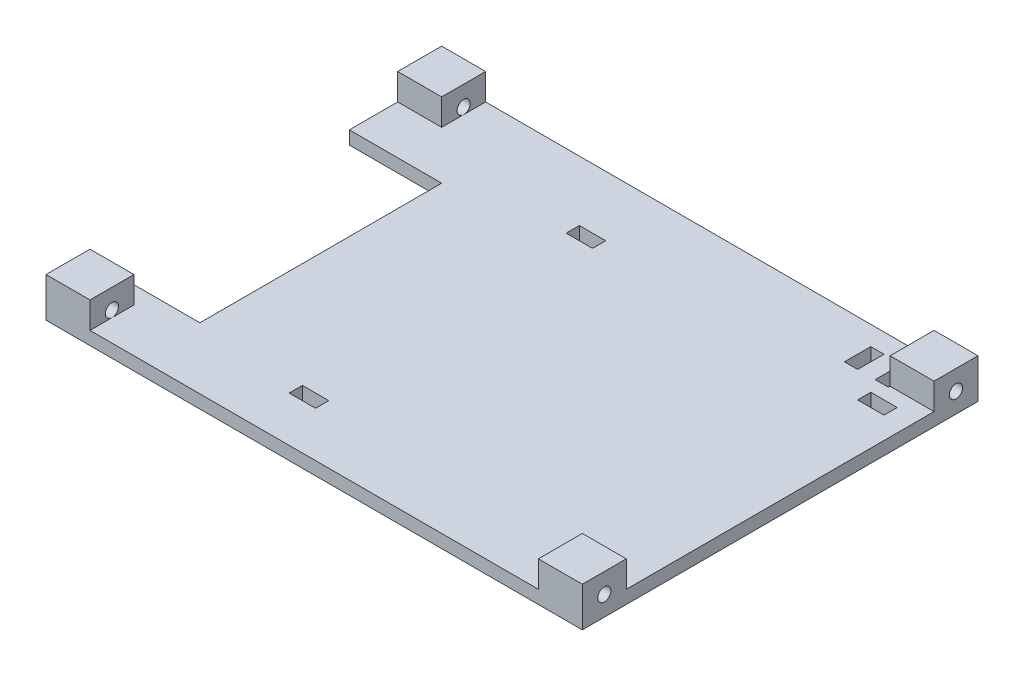
SolidWorks part; units mm, degrees
ref_plane "Front Plane" through (0, 0, 0) normal (0, 0, 1) x (1, 0, 0)
ref_plane "Top Plane" through (0, 0, 0) normal (0, 1, 0) x (1, 0, 0)
ref_plane "Right Plane" through (0, 0, 0) normal (1, 0, 0) x (0, 0, -1)
sketch "Sketch1" plane through (0, 0, 0) normal (0, 1, 0) x (1, 0, 0)
  line L1 (0, 0) -> (122, 0)
  line L2 (0, 0) -> (0, 90)
  line L3 (0, 90) -> (122, 90)
  line L4 (122, 0) -> (122, 90)
  dimension "D1" = 122
  dimension "D2" = 90
extrude "Boss-Extrude1" add sketch "Sketch1" along normal blind 3
sketch "Sketch2" plane through (0, 3, 0) normal (0, 1, 0) x (1, 0, 0)
  line L1 (0, 0) -> (10, 0)
  line L2 (0, 0) -> (0, 10)
  line L3 (0, 10) -> (7.7811, 10)
  line L4 (10, 0) -> (10, 5.7066)
  line L5 (0, 90) -> (10, 90)
  line L6 (0, 90) -> (0, 80)
  line L7 (0, 80) -> (10, 80)
  line L8 (10, 90) -> (10, 80)
  line L9 (122, 90) -> (112, 90)
  line L10 (122, 90) -> (122, 80)
  line L11 (122, 80) -> (112, 80)
  line L12 (112, 90) -> (112, 80)
  line L13 (122, 0) -> (112, 0)
  line L14 (122, 0) -> (122, 10)
  line L15 (122, 10) -> (112, 10)
  line L16 (112, 0) -> (112, 10)
  line L17 (7.7811, 10) -> (10, 10)
  line L19 (10, 10) -> (10, 5.7066)
  dimension "D10" = 10
  dimension "D11" = 10
  dimension "D12" = 10
  dimension "D13" = 10
  dimension "D14" = 10
  dimension "D15" = 10
extrude "Boss-Extrude2" add sketch "Sketch2" along normal blind 6
sketch "Sketch4" plane through (0, 0, 0) normal (-1, 0, 0) x (0, 0, 1)
  circle A0 centre (-85, 4.5) radius 1.5
  circle A1 centre (-5, 4.5) radius 1.5
  dimension "D1" = 3
  dimension "D2" = 3
extrude "Cut-Extrude2" cut sketch "Sketch4" against normal up to next
sketch "Sketch5" plane through (122, 0, 0) normal (1, 0, 0) x (0, 0, -1)
  circle A0 centre (85, 4.5) radius 1.5
  circle A1 centre (5, 4.5) radius 1.5
extrude "Cut-Extrude3" cut sketch "Sketch5" against normal up to next
ref_plane "Plane1" through (0, 13, 0) normal (0, 1, 0) x (1, 0, 0)
sketch "Sketch6" plane through (0, 13, 0) normal (0, 1, 0) x (1, 0, 0)
  line L0 (122, 10) -> (122, 80) construction
  line L1 (117, 14.0761) -> (26, 14.0761) construction
  line L2 (117, 14.0761) -> (117, 72.0761) construction
  line L3 (117, 72.0761) -> (26, 72.0761) construction
  line L4 (26, 14.0761) -> (26, 72.0761) construction
  line L5 (197.7061, -227.4768) -> (473.8742, 101.4956) construction
  dimension "D1" = 91
  dimension "D2" = 58
  dimension "D3" = 5
sketch "Sketch7" plane through (0, 3, 0) normal (0, 1, 0) x (1, 0, 0)
  line L0 (51, 76.3155) -> (45, 76.3155)
  line L1 (117, 76.6169) -> (111, 76.6169)
  line L2 (117, 76.6169) -> (117, 73.6169)
  line L3 (117, 73.6169) -> (111, 73.6169)
  line L4 (111, 76.6169) -> (111, 73.6169)
  line L5 (51, 76.3155) -> (51, 73.3155)
  line L6 (51, 73.3155) -> (45, 73.3155)
  line L7 (45, 76.3155) -> (45, 73.3155)
  line L8 (122, 10) -> (122, 80) construction
  line L9 (51, 13.3155) -> (45, 13.3155)
  line L10 (117, 13.6169) -> (111, 13.6169)
  line L11 (117, 13.6169) -> (117, 10.6169)
  line L12 (117, 10.6169) -> (111, 10.6169)
  line L13 (111, 13.6169) -> (111, 10.6169)
  line L14 (51, 13.3155) -> (51, 10.3155)
  line L15 (51, 10.3155) -> (45, 10.3155)
  line L16 (45, 13.3155) -> (45, 10.3155)
  line L17 (112, 90) -> (112, 80) construction
  line L18 (109, 79.6169) -> (112, 79.6169)
  line L19 (109, 79.6169) -> (109, 85.6169)
  line L20 (109, 85.6169) -> (112, 85.6169)
  line L21 (112, 79.6169) -> (112, 85.6169)
  line L22 (105, 79.6169) -> (102, 79.6169)
  line L23 (105, 79.6169) -> (105, 85.6169)
  line L24 (105, 85.6169) -> (102, 85.6169)
  line L25 (102, 79.6169) -> (102, 85.6169)
  line L26 (0, 80) -> (0, 10) construction
  line L27 (21, 14) -> (0, 14)
  line L28 (21, 14) -> (21, 69)
  line L29 (21, 69) -> (0, 69)
  line L30 (0, 14) -> (0, 69)
  line L31 (10, 10) -> (0, 10) construction
  point P18 (114, 73.6169)
  dimension "D1" = 3
  dimension "D2" = 6
  dimension "D3" = 3
  dimension "D4" = 6
  dimension "D5" = 60
  dimension "D6" = 5
  dimension "D7" = 3
  dimension "D8" = 6
  dimension "D9" = 3
  dimension "D10" = 6
  dimension "D11" = 60
  dimension "D12" = 5
  dimension "D13" = 60
  dimension "D14" = 6
  dimension "D15" = 6
  dimension "D16" = 3
  dimension "D17" = 3
  dimension "D18" = 4
  dimension "D19" = 0
  dimension "D20" = 3
  dimension "D21" = 21
  dimension "D22" = 55
  dimension "D23" = 4
extrude "Cut-Extrude4" cut sketch "Sketch7" against normal through all
